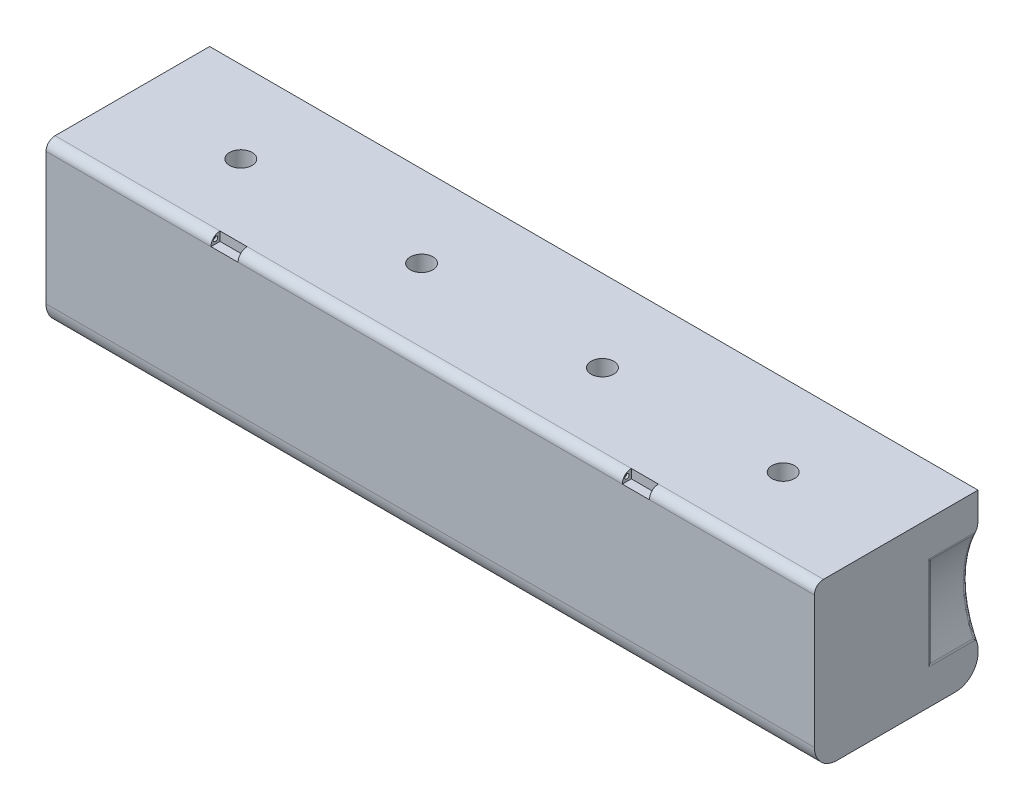
SolidWorks part; units mm, degrees
ref_plane "Front Plane" through (0, 0, 0) normal (0, 0, 1) x (1, 0, 0)
ref_plane "Top Plane" through (0, 0, 0) normal (0, 1, 0) x (1, 0, 0)
ref_plane "Right Plane" through (0, 0, 0) normal (1, 0, 0) x (0, 0, -1)
sketch "Sketch1" plane through (0, 0, 0) normal (0, 0, 1) x (1, 0, 0)
  line L0 (-42.5, 0) -> (0, 0) construction
  line L1 (-42.5, 9.05) -> (42.5, 9.05)
  line L2 (-42.5, 9.05) -> (-42.5, -9.05)
  line L3 (-42.5, -9.05) -> (42.5, -9.05)
  line L4 (42.5, 9.05) -> (42.5, -9.05)
  line L5 (0, 0) -> (0, -9.05) construction
  dimension "D1" = 85
  dimension "D2" = 18.1
extrude "Boss-Extrude1" add sketch "Sketch1" along normal blind 18.1
sketch "Sketch2" plane through (0, 0, 0) normal (0, 0, -1) x (-1, 0, 0)
  line L0 (40, -6.55) -> (40, 6.55)
  line L1 (40, 6.55) -> (-40, 6.55)
  line L2 (-40, 6.55) -> (-40, -6.55)
  line L3 (-40, -6.55) -> (40, -6.55)
extrude "Cut-Extrude1" cut sketch "Sketch2" against normal blind 17.5
sketch "Sketch3" plane through (0, 9.05, 0) normal (0, 1, 0) x (1, 0, 0)
  line L0 (-42.5, -9.05) -> (-30, -9.05) construction
  line L1 (-42.5, -18.1) -> (-42.5, 0) construction
  line L2 (42.5, -18.1) -> (42.5, 0) construction
  circle A0 centre (-30, -9.05) radius 1.25
  circle A1 centre (-10, -9.05) radius 1.25
  circle A2 centre (10, -9.05) radius 1.25
  circle A3 centre (30, -9.05) radius 1.25
  dimension "D1" = 12.5
  dimension "D2" = 2.5
  dimension "D4" = 12.5
  dimension "D3" = 4
extrude "Cut-Extrude2" cut sketch "Sketch3" against normal up to surface (2.5 mm away) up to face at (0, 6.55, 8.75)
sketch "Sketch4" plane through (0, 0, 18.1) normal (0, 0, 1) x (1, 0, 0)
  line L0 (0, 0) -> (0, 9.05) construction
  line L1 (42.5, 9.05) -> (-42.5, 9.05) construction
  line L2 (-21.25, 8.05) -> (21.25, 8.05) construction
  line L3 (-24.25, 9.05) -> (-21.25, 9.05)
  line L4 (-24.25, 9.05) -> (-24.25, 8.05)
  line L5 (-24.25, 8.05) -> (-21.25, 8.05)
  line L6 (-21.25, 9.05) -> (-21.25, 8.05)
  line L7 (24.25, 9.05) -> (21.25, 9.05)
  line L8 (24.25, 9.05) -> (24.25, 8.05)
  line L9 (24.25, 8.05) -> (21.25, 8.05)
  line L10 (21.25, 9.05) -> (21.25, 8.05)
  point P13 (0, 8.05)
  dimension "D1" = 3
  dimension "D2" = 3
  dimension "D3" = 1
  dimension "D4" = 42.5
extrude "Cut-Extrude4" cut sketch "Sketch4" against normal blind 1
sketch "Sketch11" plane through (0, 0, 18.1) normal (0, 0, 1) x (1, 0, 0)
  line L12 (-24.25, 8.05) -> (-24.25, 9.05)
  line L13 (-24.25, 9.05) -> (-42.5, 9.05)
  line L14 (-42.5, 9.05) -> (-42.5, -9.05)
  line L15 (-42.5, -9.05) -> (42.5, -9.05)
  line L16 (42.5, -9.05) -> (42.5, 9.05)
  line L17 (42.5, 9.05) -> (24.25, 9.05)
  line L18 (24.25, 9.05) -> (24.25, 8.05)
  line L19 (24.25, 8.05) -> (21.25, 8.05)
  line L20 (21.25, 8.05) -> (21.25, 9.05)
  line L21 (21.25, 9.05) -> (-21.25, 9.05)
  line L22 (-21.25, 9.05) -> (-21.25, 8.05)
  line L23 (-21.25, 8.05) -> (-24.25, 8.05)
  line L24 (-24.25, 8.05) -> (-24.25, 9.05)
  line L25 (-24.25, 9.05) -> (-42.5, 9.05)
  line L26 (-42.5, 9.05) -> (-42.5, -9.05)
  line L27 (-42.5, -9.05) -> (42.5, -9.05)
  line L28 (42.5, -9.05) -> (42.5, 9.05)
  line L29 (42.5, 9.05) -> (24.25, 9.05)
  line L30 (24.25, 9.05) -> (24.25, 8.05)
  line L31 (24.25, 8.05) -> (21.25, 8.05)
  line L32 (21.25, 8.05) -> (21.25, 9.05)
  line L33 (21.25, 9.05) -> (-21.25, 9.05)
  line L34 (-21.25, 9.05) -> (-21.25, 8.05)
  line L35 (-21.25, 8.05) -> (-24.25, 8.05)
  dimension "D1" = 0
extrude "Boss-Extrude3" add sketch "Sketch11" against normal blind 1
sketch "Sketch5" plane through (-24.25, 0, 0) normal (1, 0, 0) x (0, 0, -1)
  line L0 (-17.6, 9.05) -> (-17.6, 8.55) construction
  line L1 (-17.1, 9.05) -> (-18.1, 9.05) construction
  line L2 (-17.6, 8.55) -> (-18.1, 8.55) construction
  line L3 (-18.1, 9.05) -> (-18.1, 8.05) construction
  circle A0 centre (-17.6, 8.55) radius 0.25
  dimension "D1" = 0.5
extrude "Cut-Extrude5" cut sketch "Sketch5" against normal blind 0.25
sketch "Sketch6" plane through (-21.25, 0, 0) normal (-1, 0, 0) x (0, 0, 1)
  circle A1 centre (17.6, 8.55) radius 0.25
  circle A2 centre (17.6, 8.55) radius 0.25
  dimension "D1" = 0
extrude "Cut-Extrude6" cut sketch "Sketch6" against normal blind 0.25
sketch "Sketch7" plane through (24.25, 0, 0) normal (-1, 0, 0) x (0, 0, 1)
  circle A1 centre (17.6, 8.55) radius 0.25
  circle A2 centre (17.6, 8.55) radius 0.25
  dimension "D1" = 0
extrude "Cut-Extrude7" cut sketch "Sketch7" against normal blind 0.25
sketch "Sketch8" plane through (21.25, 0, 0) normal (1, 0, 0) x (0, 0, -1)
  circle A1 centre (-17.6, 8.55) radius 0.25
  circle A2 centre (-17.6, 8.55) radius 0.25
  dimension "D1" = 0
extrude "Cut-Extrude8" cut sketch "Sketch8" against normal blind 0.25
sketch "Sketch12" plane through (42.5, 0, 0) normal (1, 0, 0) x (0, 0, -1)
  line L0 (-18.1, -6.55) -> (-18.1, -9.05)
  line L1 (-18.1, -9.05) -> (-18.1, 9.05) construction
  line L2 (-18.1, -9.05) -> (-15.6, -9.05)
  line L3 (-18.1, -9.05) -> (0, -9.05) construction
  line L4 (-2.5, -9.05) -> (0, -9.05)
  line L5 (0, -9.05) -> (0, -6.55)
  line L6 (0, -9.05) -> (0, 9.05) construction
  arc A0 (-15.6, -9.05) -> (-18.1, -6.55) centre (-15.6, -6.55) cw
  arc A1 (0, -6.55) -> (-2.5, -9.05) centre (-2.5, -6.55) cw
  dimension "D1" = 2.5
  dimension "D2" = 2.5
extrude "Cut-Extrude9" cut sketch "Sketch12" against normal up to surface (85 mm away) up to face at (-42.5, 0, 9.05)
sketch "Sketch13" plane through (0, -9.05, 0) normal (0, -1, 0) x (1, 0, 0)
  line L0 (-42.5, 9.05) -> (-34.1357, 9.05) construction
  line L1 (-42.5, 15.6) -> (-42.5, 2.5) construction
  line L2 (-34.1357, 9.05) -> (-29.1357, 9.05) construction
  line L3 (-34.1357, 10.1757) -> (-34.1357, 8.3914) construction
  line L4 (-34.0092, 10.1757) -> (-34.0092, 8.3914)
  line L5 (-34.2621, 10.1757) -> (-34.2621, 8.3914)
  line L6 (-29.1357, 9.05) -> (-26.6357, 9.05) construction
  line L7 (-26.6357, 9.05) -> (-24.1357, 9.05) construction
  circle A0 centre (-34.1357, 9.05) radius 1.3908
  circle A1 centre (-29.1357, 9.05) radius 0.6594
  circle A2 centre (-26.6357, 9.05) radius 0.6594
  circle A3 centre (-24.1357, 9.05) radius 0.6594
  arc A4 (-33.5104, 9.9017) -> (-34.7609, 9.9017) centre (-34.1357, 9.05) cw construction
  arc A5 (-34.8688, 10.0487) -> (-33.4026, 10.0487) centre (-34.1357, 9.05) ccw
  arc A6 (-34.653, 9.7548) -> (-33.6183, 9.7548) centre (-34.1357, 9.05) ccw
  arc A7 (-34.653, 9.7548) -> (-34.8688, 10.0487) centre (-34.7609, 9.9017) ccw
  arc A8 (-33.4026, 10.0487) -> (-33.6183, 9.7548) centre (-33.5104, 9.9017) ccw
  arc A9 (-34.0092, 10.1757) -> (-34.2621, 10.1757) centre (-34.1357, 10.1757) ccw
  arc A10 (-34.2621, 8.3914) -> (-34.0092, 8.3914) centre (-34.1357, 8.3914) ccw
  circle A11 centre (-29.1357, 9.05) radius 0.4256
  circle A12 centre (-26.6357, 9.05) radius 0.4256
  circle A13 centre (-24.1357, 9.05) radius 0.4256
  point P13 (-34.1357, 7.9934)
  point P22 (-34.1357, 9.2835)
  dimension "D1" = 2.5
  dimension "D2" = 2.5
  dimension "D3" = 5
extrude "Cut-Extrude10" cut sketch "Sketch13" against normal blind 0.5
sketch "Sketch16" plane through (0, 0, 0) normal (0, 0, -1) x (-1, 0, 0)
  line L2 (-42.5, 0) -> (0, 0) construction
  line L3 (0, 0) -> (0, -9.05) construction
  line L4 (42.5, -9.05) -> (-42.5, -9.05) construction
  line L5 (-42.5, -5.0594) -> (-42.5, 5.0594)
  line L9 (-42.5, -6.55) -> (-42.5, 9.05) construction
  line L10 (42.5, -5.0594) -> (42.5, 5.0594)
  arc A2 (-42.5, 5.0594) -> (-42.5, -5.0594) centre (-53.2171, 0) cw
  arc A3 (42.5, 5.0594) -> (42.5, -5.0594) centre (53.2171, 0) ccw
extrude "Cut-Extrude11" cut sketch "Sketch16" against normal blind 5
fillet "Fillet1" radius 0.5 8 edges at (41.3658, 0, 0) (-42.5, -5.0594, 2.5) (-42.5, 5.0594, 2.5) (-42.5, 0, 5) (42.5, 5.0594, 2.5) (42.5, -5.0594, 2.5) (-41.3658, 0, 0) (42.5, 0, 5)
sketch "Sketch17" plane through (42.5, 0, 0) normal (1, 0, 0) x (0, 0, -1)
  line L0 (-18.1, 8.05) -> (-18.1, 9.05)
  line L1 (-18.1, -6.55) -> (-18.1, 9.05) construction
  line L2 (-18.1, 9.05) -> (-17.1, 9.05)
  arc A0 (-17.1, 9.05) -> (-18.1, 8.05) centre (-17.1, 8.05) ccw
  dimension "D1" = 1
extrude "Cut-Extrude12" cut sketch "Sketch17" against normal up to surface (85 mm away)
